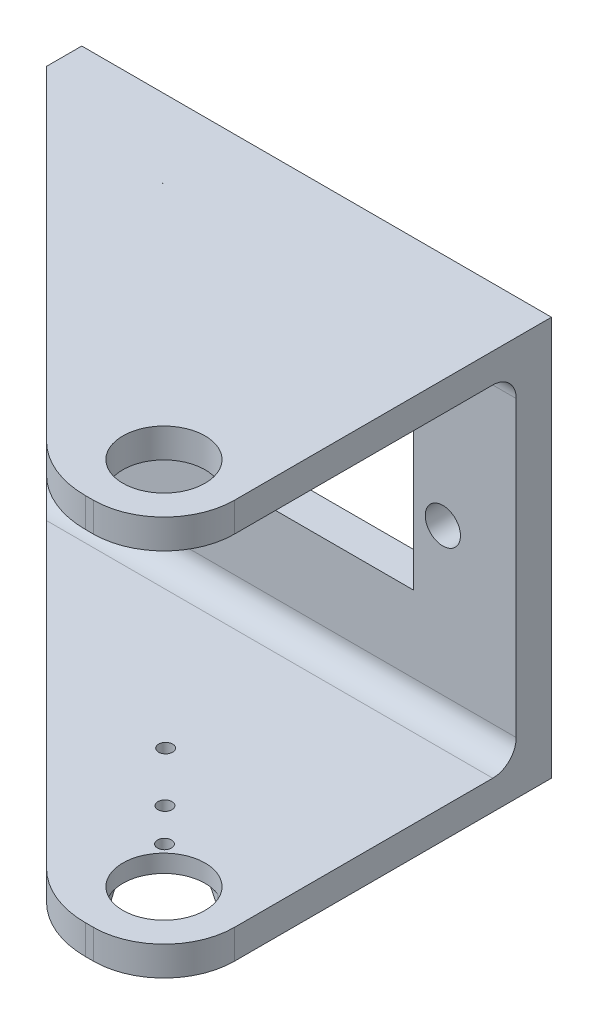
SolidWorks part; units mm, degrees
ref_plane "Plano frontal" through (0, 0, 0) normal (0, 0, 1) x (1, 0, 0)
ref_plane "Plano superior" through (0, 0, 0) normal (0, 1, 0) x (1, 0, 0)
ref_plane "Plano direito" through (0, 0, 0) normal (1, 0, 0) x (0, 0, -1)
other "Centro da massa"
sketch "Esboço1" plane through (0, 0, 0) normal (0, 0, 1) x (1, 0, 0)
  line L0 (-2.1016, 17.4595) -> (-2.1016, -16.5405) construction
  line L1 (-13.3516, 6.4595) -> (9.1484, 6.4595)
  line L2 (-13.3516, 6.4595) -> (-13.3516, -5.5405)
  line L3 (-13.3516, -5.5405) -> (9.1484, -5.5405)
  line L4 (9.1484, 6.4595) -> (9.1484, -5.5405)
  line L5 (-22.1016, 17.4595) -> (17.8984, 17.4595)
  line L6 (-22.1016, 17.4595) -> (-22.1016, -16.5405)
  line L7 (-22.1016, -16.5405) -> (17.8984, -16.5405)
  line L8 (17.8984, 17.4595) -> (17.8984, -16.5405)
  line L9 (-22.1016, 0.4595) -> (17.8984, 0.4595) construction
  line L10 (-22.1016, 17.4595) -> (17.8984, -16.5405) construction
  circle A0 centre (-16.1016, 12.3595) radius 1.5
  circle A1 centre (-16.1016, -11.4405) radius 1.5
  circle A2 centre (11.8984, -11.4405) radius 1.5
  circle A3 centre (11.8984, 12.3595) radius 1.5
  circle A4 centre (11.6484, 0.4595) radius 1.5
  circle A5 centre (-15.8516, 0.4595) radius 1.5
  point P10 (-2.1016, 6.4595)
  point P13 (-13.3516, 0.4595)
  point P24 (10.1484, 0.4595)
  dimension "D5" = 6
  dimension "D6" = 1
  dimension "D1" = 22.5
  dimension "D2" = 12
  dimension "D3" = 40
  dimension "D4" = 34
extrude "Ressalto-extrusão1" add sketch "Esboço1" along normal blind 3 contours A5 | L6 L5 L8 L7 | A4 | L2 L1 L4 L3
sketch "Esboço2" plane through (0, 0, 3) normal (0, 0, 1) x (1, 0, 0)
  line L0 (-22.1016, 14.9595) -> (17.8984, 14.9595) construction
  line L1 (-22.1016, 17.4595) -> (-22.1016, -16.5405) construction
  line L2 (17.8984, 17.4595) -> (17.8984, -16.5405) construction
  line L3 (-22.1016, 0.4595) -> (17.8984, 0.4595) construction
  line L4 (-22.1016, 17.4595) -> (17.8984, 17.4595) construction
  line L5 (-22.1016, 17.4595) -> (17.8984, 17.4595) construction
  line L6 (-22.1016, 17.4595) -> (-22.1016, 14.9595)
  line L7 (-22.1016, 14.9595) -> (17.8984, 14.9595)
  line L8 (17.8984, 14.9595) -> (17.8984, 17.4595)
  line L9 (17.8984, 17.4595) -> (-22.1016, 17.4595)
  line L10 (17.8984, -14.0405) -> (17.8984, -16.5405)
  line L11 (-22.1016, -14.0405) -> (17.8984, -14.0405)
  line L12 (-22.1016, -16.5405) -> (-22.1016, -14.0405)
  line L13 (17.8984, -16.5405) -> (-22.1016, -16.5405)
  dimension "D1" = 2.5
  dimension "D2" = 2.5
extrude "Ressalto-extrusão2" add sketch "Esboço2" along normal blind 30
sketch "Esboço3" plane through (0, -16.5405, 0) normal (0, -1, 0) x (1, 0, 0)
  line L0 (-22.1016, 3) -> (17.8984, 3) construction
  line L1 (-22.1016, 33) -> (-22.1016, 0) construction
  line L2 (17.8984, 33) -> (17.8984, 0) construction
  line L3 (-22.1016, 0) -> (17.8984, 0) construction
  line L4 (-22.1016, 3) -> (-22.1016, 8) construction
  line L6 (-22.1016, 33) -> (17.8984, 33) construction
  line L7 (7.8984, 33) -> (17.8984, 33) construction
  line L8 (17.8984, 33) -> (17.8984, 3) construction
  line L9 (-22.1016, 3) -> (7.8984, 33)
  line L11 (-22.1016, 33) -> (7.8984, 33)
  line L13 (-22.1016, 3) -> (-22.1016, 33)
  circle A0 centre (11.8984, 27) radius 3.5
  dimension "D4" = 6
  dimension "D5" = 6
  dimension "D1" = 3
  dimension "D3" = 10
extrude "Corte-extrusão1" cut sketch "Esboço3" against normal through all both and the other way through all
fillet "Filete1" radius 6 2 edges at (17.8984, 16.2095, 33) (17.8984, -15.2905, 33)
fillet "Filete2" radius 2 2 edges at (-2.1016, -14.0405, 3) (-2.1016, 14.9595, 3)
sketch "Esboço4" plane through (0, -16.5405, 0) normal (0, -1, 0) x (1, 0, 0)
  line L0 (5.1733, 23.7443) -> (-1.4541, 17.0537)
  line L1 (-1.4541, 17.0537) -> (1.906, 13.7253)
  line L2 (1.906, 13.7253) -> (8.4132, 20.2944)
  line L3 (8.3984, 27) -> (11.6898, 23.5062)
  line L4 (9.9738, 21.5795) -> (13.2903, 23.7887)
  line L5 (13.2903, 23.7887) -> (11.6898, 23.5062)
  line L6 (9.1282, 21.0162) -> (5.7681, 24.3447) construction
  line L7 (6.2536, 25.0364) -> (8.9038, 28.8118)
  line L8 (8.9038, 28.8118) -> (8.3984, 27)
  circle A0 centre (11.8984, 27) radius 3.5 construction
  arc A1 (6.2536, 25.0364) -> (5.1733, 23.7443) centre (-1.9312, 30.7818) cw
  arc A2 (9.9738, 21.5795) -> (8.4132, 20.2944) centre (15.5176, 13.2569) ccw
  dimension "D3" = 10
  dimension "D1" = 14
  dimension "D2" = 4.8
extrude "Corte-extrusão2" cut sketch "Esboço4" against normal blind 1
fillet "Filete4" radius 8 2 edges at (7.8984, -15.2905, 33) (7.8984, 16.2095, 33)
sketch "Esboço5" plane through (0, -15.5405, 0) normal (0, -1, 0) x (-1, 0, 0)
  circle A0 centre (-8.7743, -23.831) radius 0.6
  circle A1 centre (-5.9661, -20.9825) radius 0.6
  circle A2 centre (-1.7538, -16.7097) radius 0.6
extrude "Corte-extrusão3" cut sketch "Esboço5" against normal up to next
